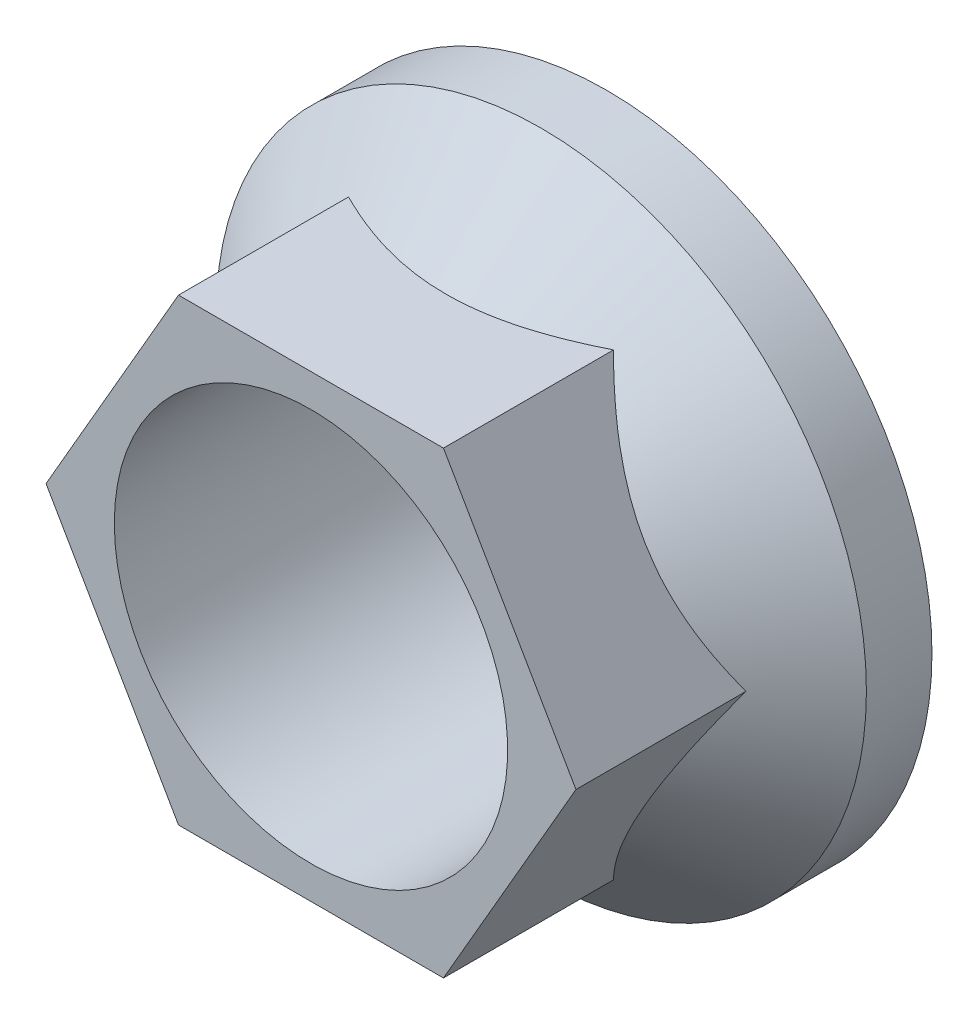
SolidWorks part; units mm, degrees
material "Alloy Steel"
ref_plane "X-Y Datum" through (0, 0, 0) normal (0, 0, 1) x (1, 0, 0)
ref_plane "X-Z Datum" through (0, 0, 0) normal (0, 1, 0) x (1, 0, 0)
ref_plane "Y-Z Datum" through (0, 0, 0) normal (1, 0, 0) x (0, 0, -1)
sketch "Sketch1" plane through (0, 0, 0) normal (1, 0, 0) x (0, 0, -1)
  line L4 (0, 4.7625) -> (-7.1628, 4.7625)
  line L5 (0, 0) -> (-39678.0303, 0) construction
  line L7 (-7.1628, 4.7625) -> (-7.1628, 5.5562)
  line L8 (-7.1628, 5.5562) -> (-3.9052, 5.5562)
  line L9 (-3.9052, 5.5562) -> (-1.5875, 7.874)
  line L10 (-1.5875, 7.874) -> (0, 7.874)
  line L11 (0, 7.874) -> (0, 4.7625)
  dimension "D1" = 9.525
  dimension "D2" = 11.1125
  dimension "D3" = 7.1628
  dimension "D4" = 15.748
  dimension "D5" = 1.5875
  dimension "D6" = 45
revolve "Revolve1" add sketch "Sketch1" angle 360 about L5
sketch "Sketch2" plane through (0, 0, 7.1628) normal (0, 0, 1) x (1, 0, 0)
  line L1 (-3.2079, 5.5563) -> (-6.4158, 0)
  line L2 (-6.4158, 0) -> (-3.2079, -5.5562)
  line L3 (-3.2079, -5.5562) -> (3.2079, -5.5563)
  line L4 (3.2079, -5.5563) -> (6.4158, 0)
  line L5 (6.4158, 0) -> (3.2079, 5.5563)
  line L6 (3.2079, 5.5563) -> (-3.2079, 5.5563)
  circle A0 centre (0, 0) radius 5.5562 construction
  circle A1 centre (0, 0) radius 4.7625 construction
  circle A2 centre (0, 0) radius 4.7625
  dimension "D1" = 11.1125
extrude "Boss-Extrude1" add sketch "Sketch2" against normal up to surface (4.1171 mm away)
move or copy body "Body-Move/Copy1" [suppressed] bodies to move or copy 102
